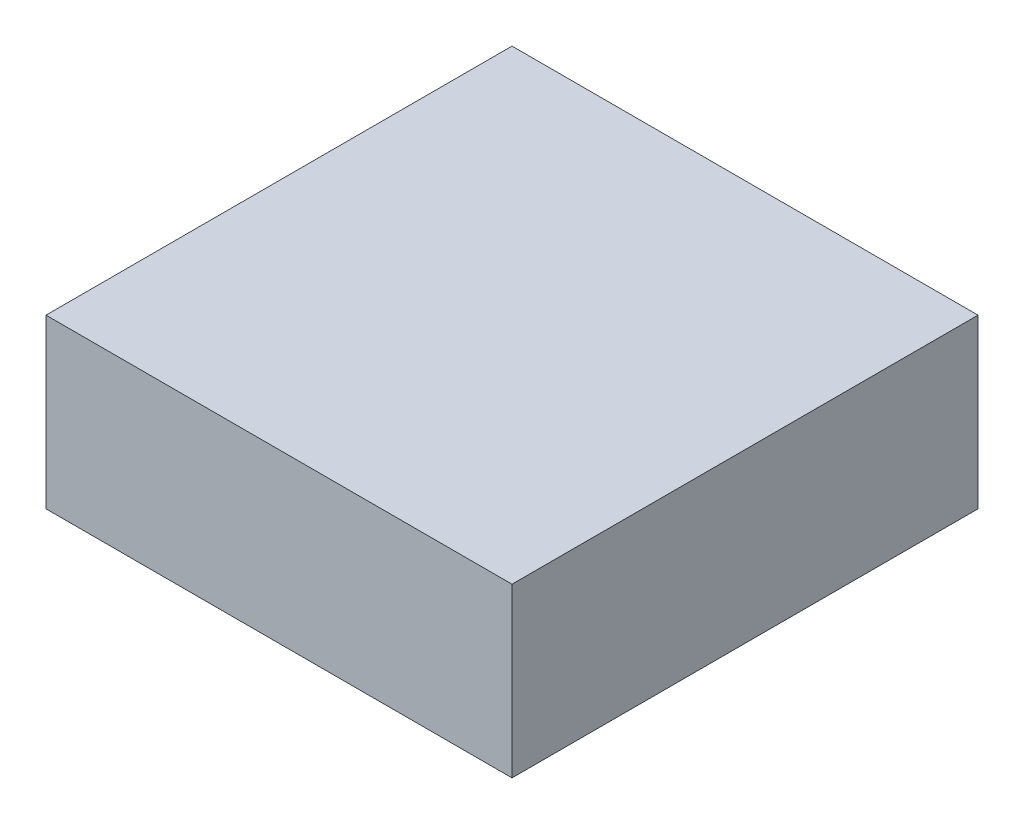
SolidWorks part; units mm, degrees
ref_plane "Спереди" through (0, 0, 0) normal (0, 0, 1) x (1, 0, 0)
ref_plane "Сверху" through (0, 0, 0) normal (0, 1, 0) x (1, 0, 0)
ref_plane "Справа" through (0, 0, 0) normal (1, 0, 0) x (0, 0, -1)
sketch "Эскиз1" plane through (0, 0, 0) normal (0, 1, 0) x (1, 0, 0)
  line L1 (-12.5, -12.5) -> (12.5, -12.5)
  line L2 (-12.5, -12.5) -> (-12.5, 12.5)
  line L3 (-12.5, 12.5) -> (12.5, 12.5)
  line L4 (12.5, -12.5) -> (12.5, 12.5)
  line L5 (-12.5, -12.5) -> (12.5, 12.5) construction
  line L6 (-12.5, 12.5) -> (12.5, -12.5) construction
  point P0 (0, 0)
  dimension "D1" = 25
extrude "Бобышка-Вытянуть1" add sketch "Эскиз1" along normal blind 9
